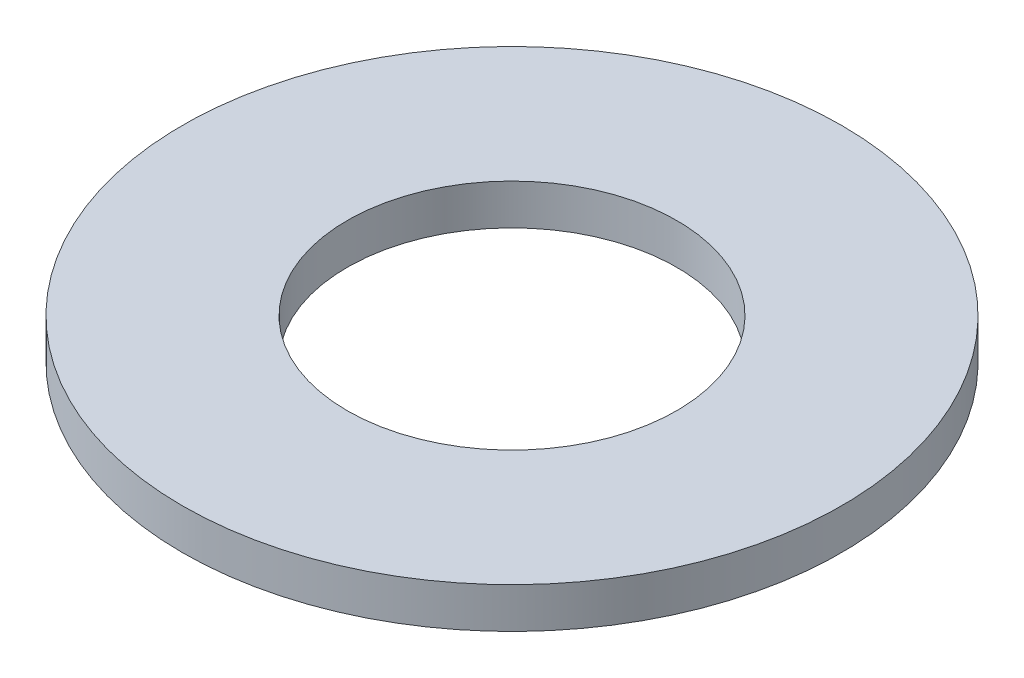
SolidWorks part; units mm, degrees
material "Galvanized Steel"
ref_plane "Front Plane" through (0, 0, 0) normal (0, 0, 1) x (1, 0, 0)
ref_plane "Top Plane" through (0, 0, 0) normal (0, 1, 0) x (1, 0, 0)
ref_plane "Right Plane" through (0, 0, 0) normal (1, 0, 0) x (0, 0, -1)
other "Configuration Table"
sketch "Sketch1" plane through (0, 0, 0) normal (0, 1, 0) x (1, 0, 0)
  circle A0 centre (0, 0) radius 3.25
  circle A1 centre (0, 0) radius 6.5
extrude "Boss-Extrude1" add sketch "Sketch1" along normal blind 0.8
